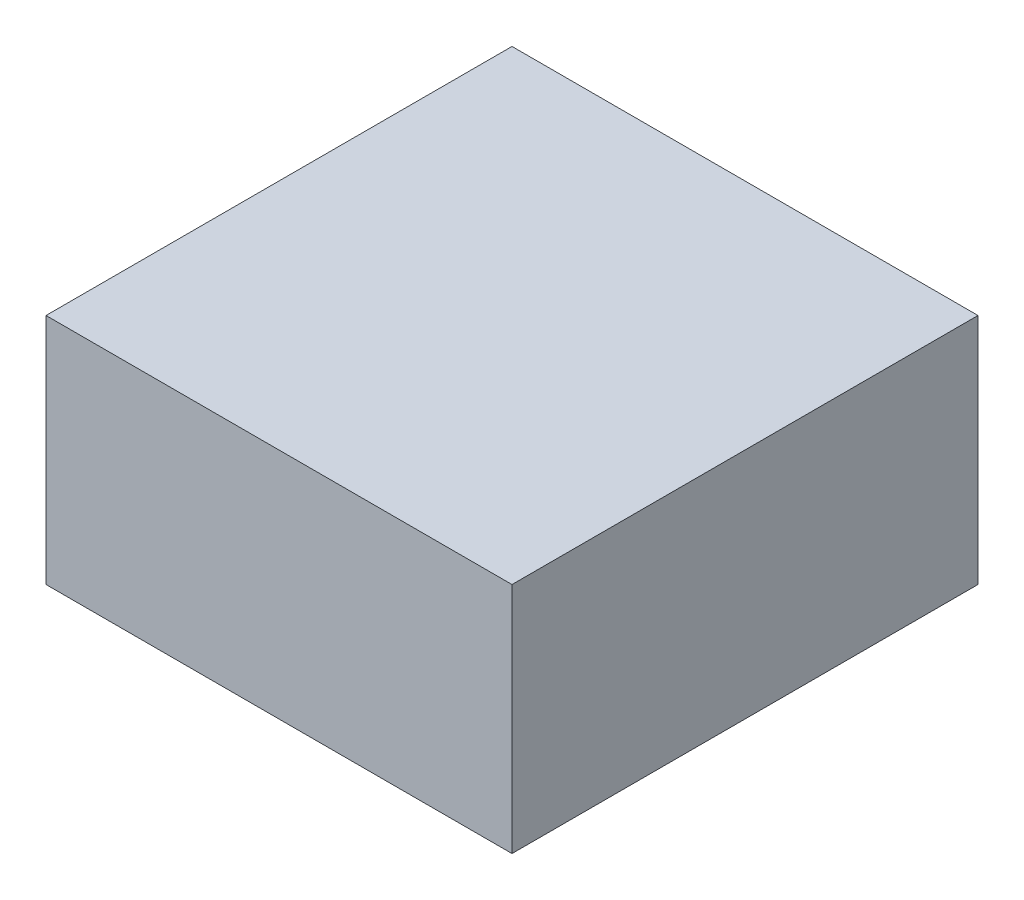
SolidWorks part; units mm, degrees
ref_plane "Front Plane" through (0, 0, 0) normal (0, 0, 1) x (1, 0, 0)
ref_plane "Top Plane" through (0, 0, 0) normal (0, 1, 0) x (1, 0, 0)
ref_plane "Right Plane" through (0, 0, 0) normal (1, 0, 0) x (0, 0, -1)
sketch "Sketch1" plane through (0, 0, 0) normal (0, 1, 0) x (1, 0, 0)
  line L1 (-6.35, -6.35) -> (6.35, -6.35)
  line L2 (-6.35, -6.35) -> (-6.35, 6.35)
  line L3 (-6.35, 6.35) -> (6.35, 6.35)
  line L4 (6.35, -6.35) -> (6.35, 6.35)
  line L5 (-6.35, -6.35) -> (6.35, 6.35) construction
  line L6 (-6.35, 6.35) -> (6.35, -6.35) construction
  point P0 (0, 0)
  dimension "D1" = 12.7
  dimension "D2" = 12.7
extrude "Boss-Extrude1" add sketch "Sketch1" along normal blind 6.35
